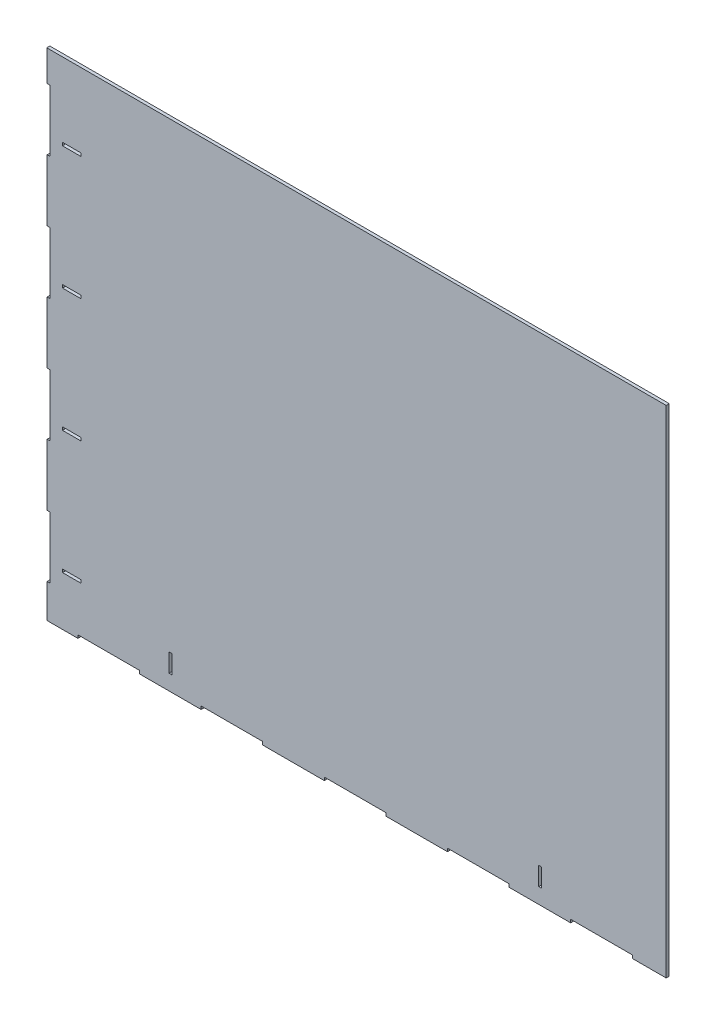
SolidWorks part; units mm, degrees
ref_plane "Front Plane" through (0, 0, 0) normal (0, 0, 1) x (1, 0, 0)
ref_plane "Top Plane" through (0, 0, 0) normal (0, 1, 0) x (1, 0, 0)
ref_plane "Right Plane" through (0, 0, 0) normal (1, 0, 0) x (0, 0, -1)
sketch "Sketch1" plane through (0, 0, 0) normal (0, 0, 1) x (1, 0, 0)
  line L0 (-201.3318, -46.6765) -> (298.6682, -46.6765) construction
  line L1 (-178.8318, 153.3369) -> (298.6682, 153.3369)
  line L2 (-201.3318, 128.3369) -> (-201.3318, 78.3101)
  line L3 (-178.8318, -246.6899) -> (-128.8318, -246.6899)
  line L4 (298.6682, 135.8235) -> (298.6682, -229.1765)
  line L5 (-201.3318, -171.6899) -> (-201.3318, -221.6899)
  line L6 (-201.3318, -249.1899) -> (-203.8318, -249.1899)
  line L7 (298.6682, -229.1765) -> (298.6682, -249.1899)
  line L8 (-178.8318, 153.3369) -> (-201.7187, 153.3369)
  line L9 (-201.3318, -171.6899) -> (-203.8318, -171.6899)
  line L10 (-201.3318, -221.6899) -> (-203.8318, -221.6899)
  line L11 (298.6682, 153.3369) -> (298.6682, 135.8235)
  line L12 (-203.8318, -249.1899) -> (-203.8318, -221.6899)
  line L13 (-201.3318, -71.6899) -> (-201.3318, -121.6899)
  line L14 (-201.3318, -121.6899) -> (-203.8318, -121.6899)
  line L15 (-203.8318, -171.6899) -> (-203.8318, -121.6899)
  line L16 (-201.3318, -21.6899) -> (-203.8318, -21.6899)
  line L17 (-201.3318, 28.3101) -> (-201.3318, -21.6899)
  line L18 (-201.3318, -71.6899) -> (-203.8318, -71.6899)
  line L19 (-203.8318, -21.6899) -> (-203.8318, -71.6899)
  line L20 (-201.3318, 78.3101) -> (-203.8318, 78.3101)
  line L21 (-201.7187, 153.3369) -> (-204.1083, 153.3369)
  line L22 (-201.3318, 28.3101) -> (-203.8318, 28.3101)
  line L23 (-203.8318, 78.3101) -> (-203.8318, 28.3101)
  line L24 (-204.1083, 153.3369) -> (-204.1083, 128.3369)
  line L25 (-204.1083, 128.3369) -> (-201.3318, 128.3369)
  line L26 (-191.3318, -106.6899) -> (-176.3318, -106.6899)
  line L27 (-191.3318, -209.1899) -> (-176.3318, -209.1899)
  line L28 (-191.3318, -209.1899) -> (-191.3318, -206.6899)
  line L29 (-191.3318, -206.6899) -> (-176.3318, -206.6899)
  line L30 (-176.3318, -209.1899) -> (-176.3318, -206.6899)
  line L31 (271.1682, -249.1899) -> (298.6682, -249.1899)
  line L32 (271.1682, -246.6899) -> (271.1682, -249.1899)
  line L33 (221.1682, -246.6899) -> (221.1682, -249.1899)
  line L34 (171.1682, -249.1899) -> (221.1682, -249.1899)
  line L35 (171.1682, -246.6899) -> (171.1682, -249.1899)
  line L36 (121.1682, -246.6899) -> (121.1682, -249.1899)
  line L37 (71.1682, -249.1899) -> (121.1682, -249.1899)
  line L38 (71.1682, -246.6899) -> (71.1682, -249.1899)
  line L39 (21.1682, -246.6899) -> (21.1682, -249.1899)
  line L40 (-28.8318, -249.1899) -> (21.1682, -249.1899)
  line L41 (-28.8318, -246.6899) -> (-28.8318, -249.1899)
  line L42 (-78.8318, -246.6899) -> (-78.8318, -249.1899)
  line L43 (-128.8318, -249.1899) -> (-78.8318, -249.1899)
  line L44 (-128.8318, -246.6899) -> (-128.8318, -249.1899)
  line L45 (-178.8318, -246.6899) -> (-178.8318, -249.1899)
  line L46 (-201.3318, -249.1899) -> (-178.8318, -249.1899)
  line L47 (-191.3318, -109.1899) -> (-191.3318, -106.6899)
  line L48 (-78.8318, -246.6899) -> (-28.8318, -246.6899)
  line L49 (21.1682, -246.6899) -> (71.1682, -246.6899)
  line L50 (121.1682, -246.6899) -> (171.1682, -246.6899)
  line L51 (221.1682, -246.6899) -> (271.1682, -246.6899)
  line L52 (-191.3318, -109.1899) -> (-176.3318, -109.1899)
  line L53 (-176.3318, -109.1899) -> (-176.3318, -106.6899)
  line L54 (-191.3318, -6.6899) -> (-176.3318, -6.6899)
  line L55 (-191.3318, -9.1899) -> (-191.3318, -6.6899)
  line L56 (-191.3318, -9.1899) -> (-176.3318, -9.1899)
  line L57 (-176.3318, -9.1899) -> (-176.3318, -6.6899)
  line L58 (-191.3318, 93.3101) -> (-176.3318, 93.3101)
  line L59 (-191.3318, 90.8101) -> (-191.3318, 93.3101)
  line L60 (-191.3318, 90.8101) -> (-176.3318, 90.8101)
  line L61 (-176.3318, 90.8101) -> (-176.3318, 93.3101)
  line L63 (-104.8318, -236.6899) -> (-102.3318, -236.6899)
  line L64 (-104.8318, -236.6899) -> (-104.8318, -221.6899)
  line L65 (-104.8318, -221.6899) -> (-102.3318, -221.6899)
  line L66 (-102.3318, -236.6899) -> (-102.3318, -221.6899)
  line L74 (195.1682, -236.6899) -> (197.6682, -236.6899)
  line L75 (195.1682, -236.6899) -> (195.1682, -221.6899)
  line L76 (195.1682, -221.6899) -> (197.6682, -221.6899)
  line L77 (197.6682, -236.6899) -> (197.6682, -221.6899)
  line L78 (-4.8318, -236.6899) -> (-2.3318, -236.6899) [skipped]
  line L79 (-4.8318, -236.6899) -> (-4.8318, -221.6899) [skipped]
  line L80 (-4.8318, -221.6899) -> (-2.3318, -221.6899) [skipped]
  line L81 (-2.3318, -236.6899) -> (-2.3318, -221.6899) [skipped]
  line L82 (95.1682, -236.6899) -> (97.6682, -236.6899) [skipped]
  line L83 (95.1682, -236.6899) -> (95.1682, -221.6899) [skipped]
  line L84 (95.1682, -221.6899) -> (97.6682, -221.6899) [skipped]
  line L85 (97.6682, -236.6899) -> (97.6682, -221.6899) [skipped]
  dimension "D1" = 27.5
  dimension "D3" = 500
  dimension "D4" = 2.5
  dimension "D5" = 2.5
  dimension "D6" = 2.5
  dimension "D7" = 2.5
  dimension "D9" = 2.5
  dimension "D10" = 50
  dimension "D8" = 2.5
  dimension "D11" = 50
  dimension "D12" = 90
  dimension "D13" = 90
  dimension "D14" = 90
  dimension "D15" = 90
  dimension "D16" = 22.5
  dimension "D17" = 50
  dimension "D20" = 50
  dimension "D21" = 10
  dimension "D22" = 40
  dimension "D23" = 2.5
  dimension "D24" = 15
  dimension "D26" = 15
  dimension "D27" = 2.5
  dimension "D28" = 10
  dimension "D29" = 24
  dimension "D25" = 4
extrude "Boss-Extrude1" add sketch "Sketch1" along normal blind 2.5
